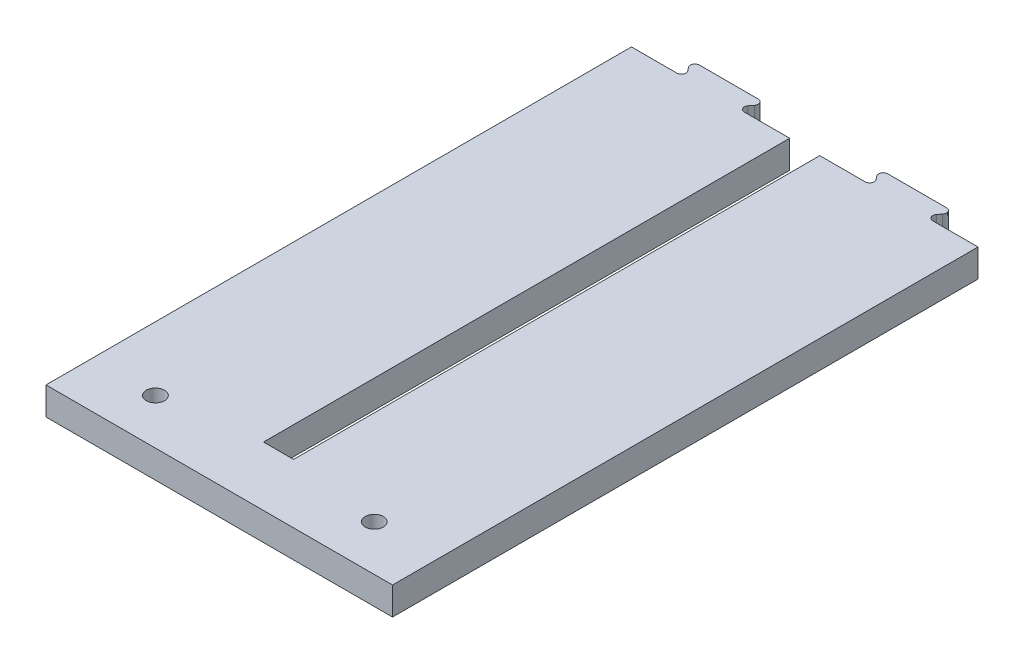
SolidWorks part; units mm, degrees
ref_plane "Front Plane" through (0, 0, 0) normal (0, 0, 1) x (1, 0, 0)
ref_plane "Top Plane" through (0, 0, 0) normal (0, 1, 0) x (1, 0, 0)
ref_plane "Right Plane" through (0, 0, 0) normal (1, 0, 0) x (0, 0, -1)
sketch "Sketch1" plane through (0, 0, 0) normal (0, 1, 0) x (1, 0, 0)
  line L1 (-19, 0) -> (19, 0)
  line L2 (-19, 0) -> (-19, 72.5)
  line L3 (-19, 72.5) -> (19, 72.5)
  line L4 (19, 0) -> (19, 72.5)
  point P5 (0, 0)
  dimension "D1" = 38
  dimension "D2" = 72.5
extrude "Boss-Extrude1" add sketch "Sketch1" along normal blind 3.05
sketch "Sketch4" plane through (0, 3.05, 0) normal (0, 1, 0) x (1, 0, 0)
  line L0 (-19, 72.5) -> (19, 72.5) construction
  line L2 (-19, 0) -> (19, 0) construction
  line L3 (1.65, 70.5) -> (-1.65, 70.5)
  line L4 (-1.65, 70.5) -> (-1.65, 69.5)
  line L5 (-1.65, 69.5) -> (1.65, 69.5)
  line L6 (1.65, 69.5) -> (1.65, 70.5)
  line L7 (0, 0) -> (0, 72.5) construction
  line L9 (1.65, 68.3) -> (-1.65, 68.3)
  line L10 (-1.65, 68.3) -> (-1.65, 6.5)
  line L11 (-1.65, 6.5) -> (1.65, 6.5)
  line L12 (1.65, 6.5) -> (1.65, 68.3)
  point P6 (0, 6.5)
  point P10 (0, 70.5)
  point P22 (0, 68.3)
  dimension "D1" = 2
  dimension "D2" = 1
  dimension "D3" = 1.2
  dimension "D4" = 3.3
  dimension "D7" = 6.5
extrude "Cut-Extrude1" cut sketch "Sketch4" against normal through all contours L5 L7 L3 L4 | L11 L7 L9 L10 | L7 L11 L12 L9 | L7 L5 L6 L3
sketch "Sketch7" plane through (0, 3.05, 0) normal (0, 1, 0) x (1, 0, 0)
  line L0 (0, 0) -> (-12, 0)
  line L1 (-19, 0) -> (19, 0) construction
  line L2 (-12, 0) -> (-12, 5)
  line L4 (0, 0) -> (0, 70) construction
  circle A0 centre (-12, 5) radius 1
  circle A2 centre (12, 5) radius 1
  dimension "D3" = 2
  dimension "D1" = 12
  dimension "D2" = 5
extrude "Cut-Extrude4" cut sketch "Sketch7" against normal through all
sketch "Sketch8" plane through (0, 3.05, 0) normal (0, 1, 0) x (1, 0, 0)
  line L0 (19, 0) -> (19, 72.5) construction
  line L1 (-19, 72.5) -> (19, 72.5)
  line L2 (-19, 72.5) -> (-19, 64.2)
  line L3 (-19, 64.2) -> (19, 64.2)
  line L4 (19, 72.5) -> (19, 64.2)
  dimension "D1" = 8.3
extrude "Cut-Extrude5" cut sketch "Sketch8" against normal through all
sketch "Sketch9" plane through (0, 3.05, 0) normal (0, 1, 0) x (1, 0, 0)
  line L0 (-19, 64.2) -> (19, 64.2) construction
  line L1 (-19, 64.2) -> (-19, 66.2) construction
  line L2 (19, 64.2) -> (19, 66.2) construction
  line L3 (-19, 66.2) -> (19, 66.2) construction
  line L4 (-19, 64.2) -> (-13, 64.2)
  line L5 (-13, 64.2) -> (-14.575, 66.2)
  line L6 (-14.575, 66.2) -> (-6.075, 66.2)
  line L7 (-6.075, 66.2) -> (-7.65, 64.2)
  line L8 (-7.65, 64.2) -> (-1.65, 64.2)
  line L9 (1.65, 64.2) -> (7.65, 64.2)
  line L10 (7.65, 64.2) -> (6.075, 66.2)
  line L11 (6.075, 66.2) -> (14.575, 66.2)
  line L12 (14.575, 66.2) -> (13, 64.2)
  line L13 (13, 64.2) -> (19, 64.2)
  line L14 (-13, 64.2) -> (-7.65, 64.2)
  line L15 (7.65, 64.2) -> (13, 64.2)
  line L16 (-19, 66.2) -> (-14.575, 66.2)
  line L17 (14.575, 66.2) -> (19, 66.2)
  line M1 (-1.65, 64.2) -> (-19, 64.2)
  line M5 (19, 64.2) -> (1.65, 64.2)
  dimension "D1" = 2
  dimension "D3" = 8.5
  dimension "D4" = 6
extrude "Boss-Extrude3" add sketch "Sketch9" against normal blind 3.05 contours L7 L6 L5 M1 | L12 L11 L10 M5
fillet "Fillet2" radius 0.5 8 edges at (13, 1.525, -64.2) (-7.65, 1.525, -64.2) (14.575, 1.525, -66.2) (7.65, 1.525, -64.2) (6.075, 1.525, -66.2) (-6.075, 1.525, -66.2) (-14.575, 1.525, -66.2) (-13, 1.525, -64.2)
